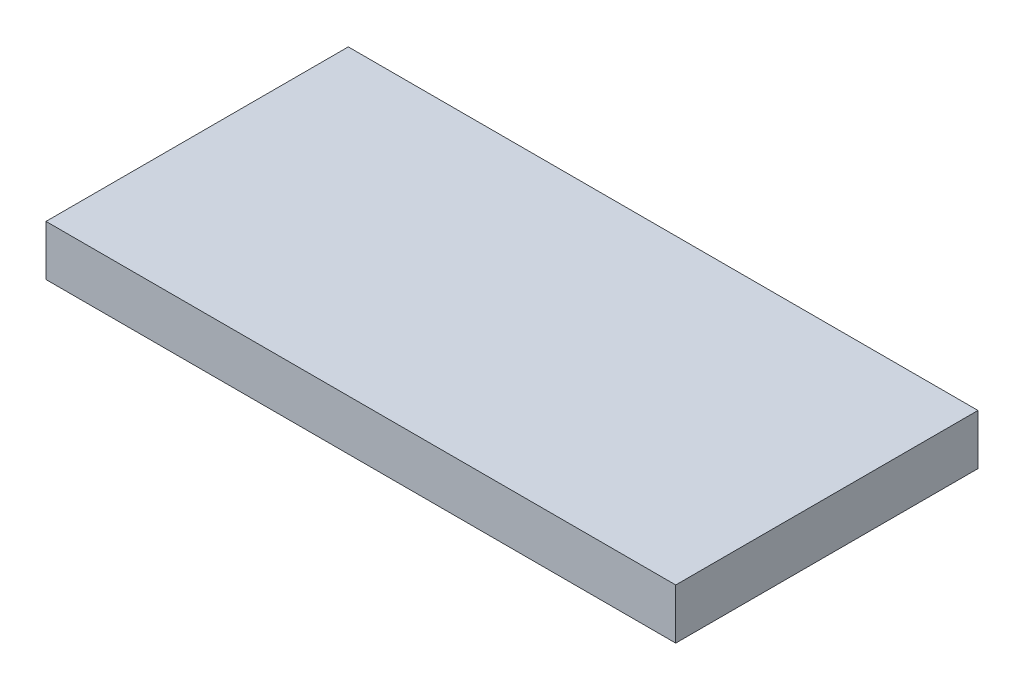
SolidWorks part; units mm, degrees
material "Fundición gris"
ref_plane "Alzado" through (0, 0, 0) normal (0, 0, 1) x (1, 0, 0)
ref_plane "Planta" through (0, 0, 0) normal (0, 1, 0) x (1, 0, 0)
ref_plane "Vista lateral" through (0, 0, 0) normal (1, 0, 0) x (0, 0, -1)
sketch "Croquis1" plane through (0, 0, 0) normal (0, 1, 0) x (1, 0, 0)
  line L1 (125, -60) -> (-125, -60)
  line L2 (125, -60) -> (125, 60)
  line L3 (125, 60) -> (-125, 60)
  line L4 (-125, -60) -> (-125, 60)
  line L5 (125, -60) -> (-125, 60) construction
  line L6 (125, 60) -> (-125, -60) construction
  point P0 (0, 0)
  dimension "D1" = 120
  dimension "D2" = 250
extrude "Saliente-Extruir1" add sketch "Croquis1" along normal blind 20
